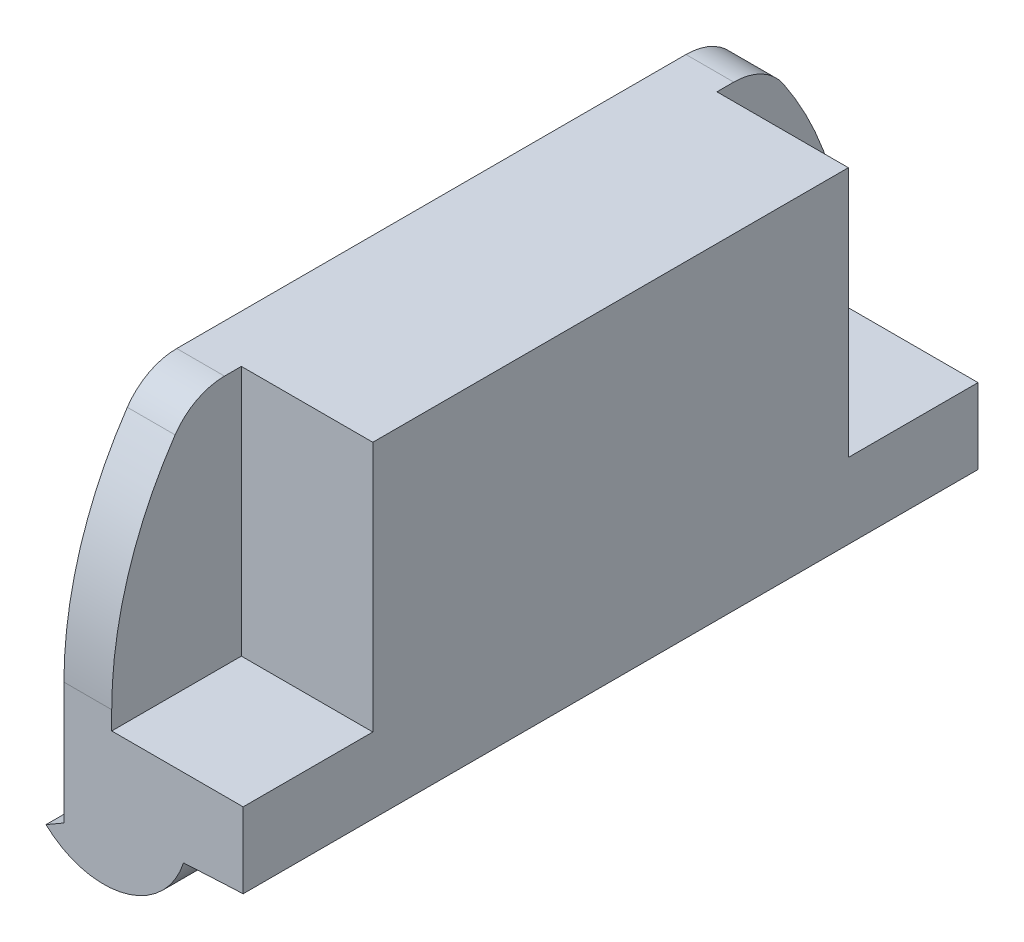
SolidWorks part; units mm, degrees
ref_plane "Front Plane" through (0, 0, 0) normal (0, 0, 1) x (1, 0, 0)
ref_plane "Top Plane" through (0, 0, 0) normal (0, 1, 0) x (1, 0, 0)
ref_plane "Right Plane" through (0, 0, 0) normal (1, 0, 0) x (0, 0, -1)
sketch "Sketch1" plane through (0, 0, 0) normal (0, 0, 1) x (1, 0, 0)
  line L0 (0, 0) -> (0.3, 0.1732)
  line L1 (0.3, 6.1075) -> (0.3, 1.7816)
  line L2 (0.3, 6.1075) -> (3.3, 6.1075)
  line L3 (3.3, 6.1075) -> (3.3, 0.6468)
  line L4 (0.3, 1.7816) -> (0.3, 0.1732)
  line L5 (0.3, 0.9774) -> (0.15, 0.0866) construction
  line L6 (2.3013, 0.5964) -> (0.3, 0.1732) construction
  line L7 (1.3155, -0.3379) -> (0.3, 0.1732) construction
  line L8 (1.3155, -0.3379) -> (3.3, 0.6468) construction
  arc A0 (3.3, 0.6468) -> (2.3013, 0.5964) centre (8.5649, -113.5554) ccw
  arc A1 (2.3013, 0.5964) -> (0, 0) centre (0.9634, 1.0207) cw
  point P9 (0.3, 1.7816)
  point P10 (0, -3.0581)
  dimension "D1" = 0.3464
  dimension "D2" = 114.3235
  dimension "D3" = 5.9342
  dimension "D6" = 1
  dimension "D4" = 3
  dimension "D5" = 5.4606
  dimension "D7" = 1.6084
  dimension "D8" = 0.9033
  dimension "D9" = 1.1369
  dimension "D10" = 2.2154
extrude "Boss-Extrude1" add sketch "Sketch1" along normal blind 12.3
sketch "Sketch2" plane through (0, 6.1075, 0) normal (0, 1, 0) x (1, 0, 0)
  line L0 (3.3, -6.15) -> (0.3, -6.15) construction
  line L1 (3.3, 0) -> (1.1, 0)
  line L2 (3.3, 0) -> (3.3, -2.17)
  line L3 (3.3, -2.17) -> (1.1, -2.17)
  line L4 (1.1, 0) -> (1.1, -2.17)
  line L5 (3.3, -12.3) -> (3.3, 0) construction
  line L6 (0.3, -12.3) -> (0.3, 0) construction
  line L7 (3.3, -10.13) -> (1.1, -10.13)
  line L8 (3.3, -12.3) -> (3.3, -10.13)
  line L9 (3.3, -12.3) -> (1.1, -12.3)
  line L10 (1.1, -12.3) -> (1.1, -10.13)
  dimension "D1" = 2.17
  dimension "D2" = 2.2
extrude "Cut-Extrude1" cut sketch "Sketch2" against normal blind 4.2
sketch "Sketch4" plane through (0.3, 0, 0) normal (-1, 0, 0) x (0, 0, 1)
  line L0 (12.3, 0.1732) -> (12.3, 2.2159) construction
  line L1 (12.3, 6.1075) -> (12.3, 0.1732) construction
  line L2 (1.8884, 6.1075) -> (10.4116, 6.1075) construction
  line L3 (12.3, 6.1075) -> (0, 6.1075) construction
  line L4 (6.15, 6.1075) -> (6.15, 0.1732) construction
  line L5 (12.3, 0.1732) -> (0, 0.1732) construction
  line L6 (11.2391, 5.669) -> (10.4116, 6.1075) construction
  line L7 (10.4116, 6.1075) -> (12.3, 6.1075)
  line L8 (12.3, 6.1075) -> (12.3, 2.2159)
  line L9 (1.8884, 6.1075) -> (0, 6.1075)
  line L10 (0, 6.1075) -> (0, 2.2159)
  arc A0 (12.3, 2.2159) -> (11.2391, 5.669) centre (6.1496, 2.2159) ccw
  arc A1 (11.2391, 5.669) -> (10.4116, 6.1075) centre (10.4119, 5.1078) ccw
  arc A2 (1.0609, 5.669) -> (1.8884, 6.1075) centre (1.8881, 5.1078) cw
  arc A3 (0, 2.2159) -> (1.0609, 5.669) centre (6.1504, 2.2159) cw
  dimension "D1" = 8.5232
  dimension "D2" = 0.9365
  dimension "D3" = 3.6124
  dimension "D4" = 3.6665
extrude "Cut-Extrude3" cut sketch "Sketch4" against normal up to surface (0.8 mm away) up to face at (1.1, 4.0075, 11.215)
sketch "Sketch5" plane through (0.3, 0, 0) normal (-1, 0, 0) x (0, 0, 1)
  line L0 (6.15, 1.7816) -> (6.15, 0.1732) construction
  line L1 (4.65, 2.7816) -> (7.65, 2.7816)
  line L2 (4.65, 2.7816) -> (4.65, 1.7816)
  line L3 (4.65, 1.7816) -> (7.65, 1.7816)
  line L4 (7.65, 2.7816) -> (7.65, 1.7816)
  line L5 (12.3, 0.1732) -> (0, 0.1732) construction
  dimension "D1" = 1.6084
  dimension "D2" = 3
  dimension "D3" = 1
extrude "Boss-Extrude2" add sketch "Sketch5" along normal blind 0.4
sketch "Sketch6" plane through (0, 0, 7.65) normal (0, 0, 1) x (1, 0, 0)
  line L0 (0.3, 2.7816) -> (0.3, 4.3732)
  line L1 (0.3, 5.669) -> (0.3, 2.2159) construction
  line L2 (0.3, 4.3732) -> (-0.1, 2.7816)
  line L3 (-0.1, 2.7816) -> (0.3, 2.7816)
  dimension "D1" = 1.5916
extrude "Boss-Extrude3" add sketch "Sketch6" against normal up to surface (3 mm away) up to face at (0.1, 2.2816, 4.65)
